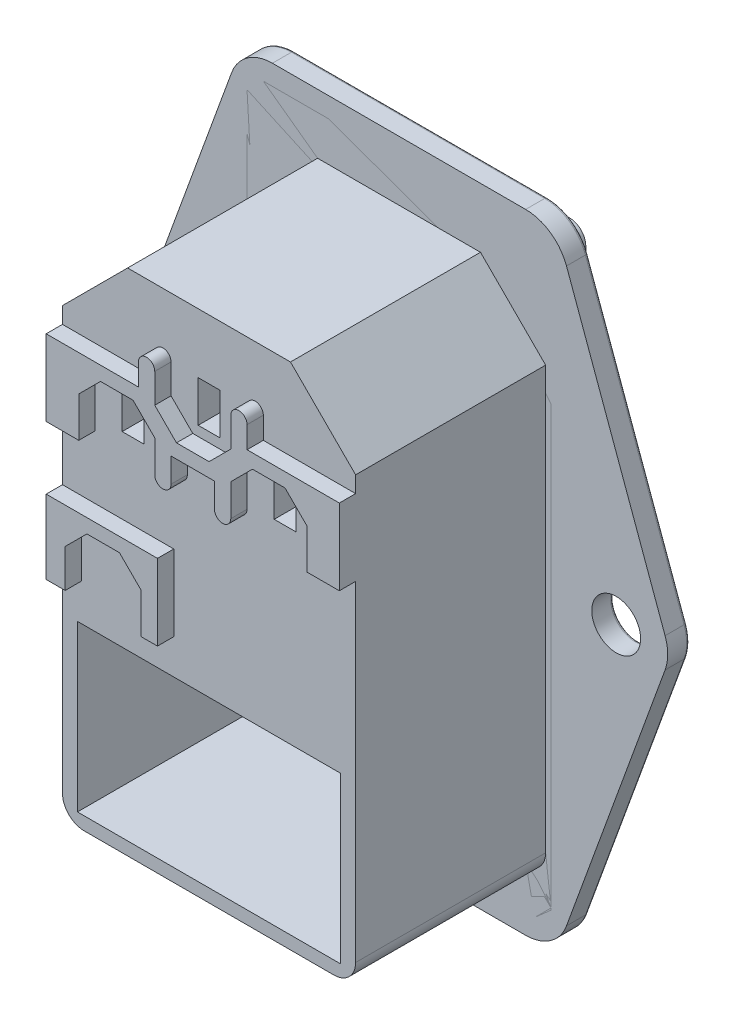
SolidWorks part; units mm, degrees
other "Mounting Face"
other "Base" parameters "D5"=2, "D1"=42.2954, "D2"=25.6387, "D3"=15.1187, "D4"=23.316, "D7"=6, "D8"=6, "D9"=0.5, "D10"=0.5, "D11"=0.5, "D12"=0.5, "D13"=0.5, "D14"=0.5, "D15"=0.5, "D16"=0.5, "D6"=2.1466, "D17"=2.5, "D18"=2.5, "D19"=4.5, "D20"=4.5, "D21"=7, "D22"=7, "D23"=31.6614, "D24"=31.6614, "D25"=2.5, "D26"=2.5, "D27"=4.5, "D28"=4.5, "D29"=9.5, "D30"=9.5, "D31"=28.4118, "D32"=28.4118, "D33"=12.05, "D34"=13.05, "D35"=13.05, "D36"=16.05, "D37"=16.05, "D38"=19.05, "D39"=19.05, "D40"=5, "D41"=5, "D42"=5, "D43"=4, "D44"=4, "D45"=4, "D46"=4, "D47"=13.55, "D48"=9.55, "D49"=5, "D50"=2, "D51"=2, "D52"=11
ref_plane "Front Plane" through (0, 0, 0) normal (0, 0, 1) x (1, 0, 0)
ref_plane "Top Plane" through (0, 0, 0) normal (0, 1, 0) x (1, 0, 0)
ref_plane "Right Plane" through (0, 0, 0) normal (1, 0, 0) x (0, 0, -1)
sketch "Sketch1" plane through (0, 0, 0) normal (0, 0, 1) x (1, 0, 0)
  line L0 (-13.5, 17.45) -> (-7.5, 23.45)
  line L1 (-7.5, 23.45) -> (7.5, 23.45)
  line L2 (-13.5, 17.45) -> (-13.5, -21.45)
  line L3 (-11.5, -23.45) -> (11.5, -23.45)
  line L4 (13.5, 17.45) -> (13.5, -21.45)
  line L5 (7.5, 23.45) -> (13.5, 17.45)
  arc A0 (11.5, -23.45) -> (13.5, -21.45) centre (11.5, -21.45) ccw
  arc A1 (-13.5, -21.45) -> (-11.5, -23.45) centre (-11.5, -21.45) ccw
  point P0 (-13.5, 23.45)
  point P3 (13.5, 23.45)
  dimension "D1" = 46.9
  dimension "D2" = 27
  dimension "D3" = 13.5
  dimension "D4" = 23.45
extrude "Base Extrude" add sketch "Sketch1" along normal blind 17.5
sketch "Sketch2" plane through (0, 0, 0) normal (0, 0, -1) x (-1, 0, 0)
  line L0 (-13.5, -21.45) -> (-13.5, 17.45) construction
  line L1 (-12.12, -7.05) -> (12.12, -7.05)
  line L2 (-12.12, -7.05) -> (-12.12, -22.25)
  line L3 (-12.12, -22.25) -> (12.12, -22.25)
  line L4 (12.12, -7.05) -> (12.12, -22.25)
  line L5 (13.5, 17.45) -> (13.5, -21.45) construction
  line L7 (11.5, -23.45) -> (-11.5, -23.45) construction
  point P4 (0, -7.05)
  dimension "D1" = 15.2
  dimension "D2" = 1.2
  dimension "D3" = 1.38
  dimension "D4" = 1.38
extrude "Switch Cavity" cut sketch "Sketch2" against normal blind 17.5
sketch "Sketch3" plane through (0, 0, 0) normal (0, 0, -1) x (-1, 0, 0)
  line L0 (-11.6622, 28.95) -> (11.6622, 28.95)
  line L1 (15.421, 26.3181) -> (24.5021, 1.3681)
  line L2 (24.5021, -1.3681) -> (15.421, -26.3181)
  line L3 (11.6622, -28.95) -> (-11.6622, -28.95)
  line L4 (-7.5, 23.45) -> (7.5, 23.45) construction
  line L5 (11.5, -23.45) -> (-11.5, -23.45) construction
  line L6 (0, 36.3877) -> (0, -35.7731) construction
  line L7 (-24.5021, -1.3681) -> (-15.421, -26.3181)
  line L8 (-15.421, 26.3181) -> (-24.5021, 1.3681)
  arc A0 (24.5021, 1.3681) -> (24.5021, -1.3681) centre (20.7433, 0) cw
  arc A1 (15.421, -26.3181) -> (11.6622, -28.95) centre (11.6622, -24.95) cw
  arc A2 (11.6622, 28.95) -> (15.421, 26.3181) centre (11.6622, 24.95) cw
  arc A3 (-15.421, -26.3181) -> (-11.6622, -28.95) centre (-11.6622, -24.95) ccw
  arc A4 (-24.5021, 1.3681) -> (-24.5021, -1.3681) centre (-20.7433, 0) ccw
  arc A5 (-11.6622, 28.95) -> (-15.421, 26.3181) centre (-11.6622, 24.95) ccw
  point P15 (25, 0)
  point P18 (14.4631, -28.95)
  point P21 (14.4631, 28.95)
  point P23 (0, -28.95)
  point P31 (0, 28.95)
  dimension "D5" = 4
  dimension "D1" = 5.5
  dimension "D2" = 5.5
  dimension "D3" = 25
  dimension "D4" = 20
extrude "Mounting Face Extrude" add sketch "Sketch3" along normal blind 2 separate body
sketch "Sketch4" plane through (0, 0, -2) normal (0, 0, -1) x (-1, 0, 0)
  line L1 (-12.5, 27.1) -> (12.5, 27.1)
  line L2 (-14, 25.6) -> (-14, -25.6)
  line L3 (-12.5, -27.1) -> (12.5, -27.1)
  line L4 (14, 25.6) -> (14, -25.6)
  arc A0 (12.5, -27.1) -> (14, -25.6) centre (12.5, -25.6) ccw
  arc A1 (-14, -25.6) -> (-12.5, -27.1) centre (-12.5, -25.6) ccw
  arc A2 (12.5, 27.1) -> (14, 25.6) centre (12.5, 25.6) cw
  arc A3 (-12.5, 27.1) -> (-14, 25.6) centre (-12.5, 25.6) ccw
  point P7 (14, -27.1)
  point P12 (14, 27.1)
  point P15 (-14, 27.1)
  dimension "D5" = 1.5
  dimension "D1" = 28
  dimension "D2" = 54.2
  dimension "D3" = 14
  dimension "D4" = 27.1
extrude "Front Face" add sketch "Sketch4" along normal blind 1.2 and the other way up to surface (2 mm away) other way up to face at (0, -14.65, 0)
sketch "Mounting Hole Positions Sketch" plane through (0, 0, -2) normal (0, 0, -1) x (-1, 0, 0)
  point P0 (-20, 0)
  point P1 (20, 0)
  dimension "D1" = 20
  dimension "D2" = 20
hole_wizard "Ø4.5 (4.5) Diameter Hole1" positions "Sketch7" profile "Sketch8" hole size "Ø4.5" standard "ANSI Metric" end condition through all
sketch "Sketch7" plane through (0, 0, -2) normal (0, 0, -1) x (-1, 0, 0)
  point P0 (-20, 0)
  point P3 (20, 0)
sketch "Sketch8" plane through (20, 0, -2) normal (1, 0, 0) x (0, 1, 0)
  line L0 (0, 0) -> (0, 19.5)
  line L1 (0, 19.5) -> (2.25, 19.5)
  line L2 (2.25, 19.5) -> (2.25, 0)
  line L5 (2.25, 0) -> (0, 0)
  line L11 (0, -6.35) -> (0, 107.95) construction
  dimension "Thru Hole Dia." = 4.5
  dimension "Thru Hole Depth" = 19.5
sketch "Sketch9" plane through (0, 0, -3.2) normal (0, 0, -1) x (-1, 0, 0)
  line L0 (-11.6622, -28.95) -> (11.6622, -28.95) construction
  line L1 (-12.5, 4.05) -> (12.5, 4.05)
  line L2 (-12.5, 4.05) -> (-12.5, -4.95)
  line L3 (-12.5, -4.95) -> (12.5, -4.95)
  line L4 (12.5, 4.05) -> (12.5, -4.95)
  line L5 (11.6622, 28.95) -> (-11.6622, 28.95) construction
  point P9 (0, 4.05)
  dimension "D1" = 9
  dimension "D2" = 24
  dimension "D3" = 24.9
  dimension "D4" = 25
extrude "Fuse Slot Cut" cut sketch "Sketch9" against normal blind 18
sketch "Sketch10" plane through (0, 0, -3.2) normal (0, 0, -1) x (-1, 0, 0)
  line L1 (-9.65, -7.05) -> (9.65, -7.05)
  line L2 (-10.65, -8.05) -> (-10.65, -21.35)
  line L3 (-9.65, -22.35) -> (9.65, -22.35)
  line L4 (10.65, -8.05) -> (10.65, -21.35)
  line L5 (-12.5, -27.1) -> (12.5, -27.1) construction
  arc A0 (9.65, -7.05) -> (10.65, -8.05) centre (9.65, -8.05) cw
  arc A1 (9.65, -22.35) -> (10.65, -21.35) centre (9.65, -21.35) ccw
  arc A2 (-10.65, -21.35) -> (-9.65, -22.35) centre (-9.65, -21.35) ccw
  arc A3 (-9.65, -7.05) -> (-10.65, -8.05) centre (-9.65, -8.05) ccw
  point P4 (0, -7.05)
  point P10 (10.65, -7.05)
  point P15 (-10.65, -22.35)
  point P18 (-10.65, -7.05)
  dimension "D4" = 1
  dimension "D1" = 21.3
  dimension "D2" = 15.3
  dimension "D3" = 4.75
extrude "Cut-Extrude3" cut sketch "Sketch10" against normal blind 2.25
sketch "Sketch11" plane through (0, 0, -0.95) normal (0, 0, -1) x (-1, 0, 0)
  line L1 (-9.5, -8.05) -> (9.5, -8.05)
  line L2 (-9.5, -8.05) -> (-9.5, -21.25)
  line L3 (-9.5, -21.25) -> (9.5, -21.25)
  line L4 (9.5, -8.05) -> (9.5, -21.25)
  line L7 (9.65, -7.05) -> (-9.65, -7.05) construction
  point P4 (0, -8.05)
  dimension "D1" = 19
  dimension "D2" = 13.2
  dimension "D3" = 1
extrude "Cut-Extrude4" cut sketch "Sketch11" against normal up to surface (18.45 mm away) up to face at (0, -14.65, 17.5)
sketch "Sketch12" plane through (0, 0, -3.2) normal (0, 0, -1) x (-1, 0, 0)
  line L0 (0, -2.1517) -> (0, 39.5345) construction
  line L1 (-6.7, 22.35) -> (6.7, 22.35)
  line L2 (6.7, 22.35) -> (12.2, 16.85)
  line L3 (12.2, 16.85) -> (12.2, 8.55)
  line L4 (9.7, 6.05) -> (-9.7, 6.05)
  line L6 (12.5, 4.05) -> (-12.5, 4.05) construction
  line L7 (14, -25.6) -> (14, 25.6) construction
  line L8 (-6.7, 22.35) -> (-12.2, 16.85)
  line L9 (-12.2, 16.85) -> (-12.2, 8.55)
  line L10 (12.5, 27.1) -> (-12.5, 27.1) construction
  arc A0 (12.2, 8.55) -> (9.7, 6.05) centre (9.7, 8.55) cw
  arc A1 (-12.2, 8.55) -> (-9.7, 6.05) centre (-9.7, 8.55) ccw
  point P8 (0, 22.35)
  point P10 (0, 6.05)
  point P25 (0, 6.05)
  dimension "D6" = 2.5
  dimension "D1" = 135
  dimension "D2" = 4.75
  dimension "D3" = 2
  dimension "D4" = 1.8
  dimension "D5" = 5.5
extrude "Cut-Extrude6" cut sketch "Sketch12" against normal blind 19.35
sketch "Sketch14" plane through (0, 0, 16.15) normal (0, 0, -1) x (-1, 0, 0)
  line L1 (-6.7, 22.35) -> (-4.7, 22.35)
  line L4 (-4.7, 22.35) -> (-4.7, 19.85)
  line L5 (-6.7, 19.85) -> (-6.7, 22.35)
  line L6 (0, 7.5639) -> (0, 19.85) construction
  line L7 (4.7, 22.35) -> (4.7, 19.85)
  line L8 (6.7, 22.35) -> (4.7, 22.35)
  line L9 (6.7, 19.85) -> (6.7, 22.35)
  arc A1 (-4.7, 19.85) -> (-6.7, 19.85) centre (-5.7, 19.85) cw
  arc A2 (4.7, 19.85) -> (6.7, 19.85) centre (5.7, 19.85) ccw
  dimension "D2" = 2
  dimension "D3" = 1
  dimension "D1" = 2.5
  dimension "D4" = 19.85
extrude "Boss-Extrude6" add sketch "Sketch14" along normal blind 2.75
sketch "Sketch15" plane through (0, 0, 16.15) normal (0, 0, -1) x (-1, 0, 0)
  line L0 (0, 30.8271) -> (0, -16.5553) construction
  line L1 (-28.4118, 12.05) -> (31.6614, 12.05) construction
  line L2 (-9.7, 6.05) -> (9.7, 6.05) construction
  line L3 (-28.4118, 16.05) -> (31.6614, 16.05) construction
  point P9 (-7, 12.05)
  point P10 (7, 12.05)
  point P11 (0, 16.05)
  dimension "D3" = 14
  dimension "D1" = 6
  dimension "D2" = 4
  dimension "D4" = 7
sketch "Sketch16" plane through (0, 0, 16.15) normal (0, 0, 1) x (1, 0, 0)
  line L0 (0, 30.8271) -> (0, -16.5553) construction
  line L1 (-28.4118, 12.05) -> (31.6614, 12.05) construction
  line L2 (2.5, 18.55) -> (2.5, 13.55)
  line L3 (-28.4118, 16.05) -> (31.6614, 16.05) construction
  line L4 (2, 19.05) -> (-2, 19.05)
  line L5 (9, 15.05) -> (5, 15.05)
  line L6 (9.5, 14.55) -> (9.5, 9.55)
  line L7 (9, 9.05) -> (5, 9.05)
  line L8 (4.5, 14.55) -> (4.5, 9.55)
  line L9 (2, 13.05) -> (-2, 13.05)
  line L10 (-2.5, 18.55) -> (-2.5, 13.55)
  line L11 (-4.5, 14.55) -> (-4.5, 9.55)
  line L12 (-5, 15.05) -> (-9, 15.05)
  line L13 (-5, 9.05) -> (-9, 9.05)
  line L14 (-9.5, 14.55) -> (-9.5, 9.55)
  arc A0 (5, 9.05) -> (4.5, 9.55) centre (5, 9.55) cw
  arc A1 (5, 15.05) -> (4.5, 14.55) centre (5, 14.55) ccw
  arc A2 (9, 15.05) -> (9.5, 14.55) centre (9, 14.55) cw
  arc A3 (9.5, 9.55) -> (9, 9.05) centre (9, 9.55) cw
  arc A4 (2, 19.05) -> (2.5, 18.55) centre (2, 18.55) cw
  arc A5 (-2, 13.05) -> (-2.5, 13.55) centre (-2, 13.55) cw
  arc A6 (2.5, 13.55) -> (2, 13.05) centre (2, 13.55) cw
  arc A7 (-2, 19.05) -> (-2.5, 18.55) centre (-2, 18.55) ccw
  arc A8 (-5, 15.05) -> (-4.5, 14.55) centre (-5, 14.55) cw
  arc A9 (-9, 9.05) -> (-9.5, 9.55) centre (-9, 9.55) cw
  arc A10 (-4.5, 9.55) -> (-5, 9.05) centre (-5, 9.55) cw
  arc A11 (-9, 15.05) -> (-9.5, 14.55) centre (-9, 14.55) ccw
  point P9 (-7, 12.05)
  point P10 (7, 12.05)
  point P11 (0, 16.05)
  point P18 (4.5, 15.05)
  point P21 (9.5, 15.05)
  point P24 (9.5, 9.05)
  dimension "D3" = 14
  dimension "D2" = 4
  dimension "D4" = 7
  dimension "D8" = 0.5
  dimension "D1" = 5
  dimension "D5" = 2.5
  dimension "D6" = 6
  dimension "D7" = 3
  dimension "D19" = 4.5
  dimension "D20" = 9.05
  dimension "D21" = 9.05
  dimension "D22" = 4
  dimension "D33" = 4
  dimension "D36" = 6
  dimension "D37" = 5
  dimension "D40" = 5
  dimension "D41" = 5
  dimension "D42" = 5
  dimension "D43" = 4
  dimension "D44" = 4
  dimension "D45" = 4
  dimension "D46" = 4
  dimension "D47" = 13.55
  dimension "D48" = 9.55
  dimension "D49" = 5
  dimension "D50" = 2
  dimension "D51" = 2
  dimension "D52" = 11
extrude "Boss-Extrude7" add sketch "Sketch16" against normal up to surface (2.75 mm away) up to face at (5.7, 20.85, 13.4)
sketch "Sketch18" plane through (0, 0, 13.4) normal (0, 0, -1) x (-1, 0, 0)
  line L0 (-28.4118, 12.05) -> (31.6614, 12.05) construction
  line L5 (-8, 13.95) -> (-6, 13.95)
  line L6 (-8, 13.95) -> (-8, 10.15)
  line L7 (-8, 10.15) -> (-6, 10.15)
  line L8 (-6, 13.95) -> (-6, 10.15)
  line L13 (6, 13.95) -> (8, 13.95)
  line L14 (8, 13.95) -> (8, 10.15)
  line L15 (6, 13.95) -> (6, 10.15)
  line L16 (6, 10.15) -> (8, 10.15)
  line L17 (-1, 17.95) -> (1, 17.95)
  line L18 (1, 17.95) -> (1, 14.15)
  line L19 (-1, 17.95) -> (-1, 14.15)
  line L20 (-1, 14.15) -> (1, 14.15)
  dimension "D1" = 3.8
  dimension "D2" = 2
  dimension "D3" = 1.9
  dimension "D4" = 1
extrude "Cut-Extrude7" cut sketch "Sketch18" against normal up to surface (4.1 mm away) up to face at (0, -14.65, 17.5)
sketch "Sketch19" plane through (0, 0, 13.4) normal (0, 0, -1) x (-1, 0, 0)
  line L0 (-5, 15.05) -> (-9, 15.05) construction
  line L1 (-8, 15.05) -> (-6, 15.05)
  line L2 (-8, 15.05) -> (-8, 9.05)
  line L3 (-8, 9.05) -> (-6, 9.05)
  line L4 (-6, 15.05) -> (-6, 9.05)
  line L5 (-5, 9.05) -> (-9, 9.05) construction
  line L6 (-1, 19.05) -> (-1, 13.05)
  line L7 (1, 19.05) -> (1, 13.05)
  line L8 (-1, 13.05) -> (1, 13.05)
  line L9 (-1, 19.05) -> (1, 19.05)
  line L10 (6, 15.05) -> (6, 9.05)
  line L11 (8, 15.05) -> (8, 9.05)
  line L12 (6, 9.05) -> (8, 9.05)
  line L13 (6, 15.05) -> (8, 15.05)
  dimension "D1" = 2
  dimension "D2" = 1
extrude "Cut-Extrude8" cut sketch "Sketch19" against normal blind 1.5
ref_plane "Plane1" through (0, -0.45, 0) normal (0, 1, 0) x (1, 0, 0)
sketch "Sketch21" plane through (0, 0, -3.2) normal (0, 0, -1) x (-1, 0, 0)
  line L0 (-9.7, 6.05) -> (9.7, 6.05) construction
  line L1 (-2.08, 6.05) -> (2.08, 6.05)
  line L2 (-2.08, 6.05) -> (-2.08, 4.05)
  line L3 (-2.08, 4.05) -> (2.08, 4.05)
  line L4 (2.08, 6.05) -> (2.08, 4.05)
  line L5 (12.5, 4.05) -> (-12.5, 4.05) construction
  dimension "D1" = 4.16
  dimension "D2" = 2.08
extrude "Cut-Extrude10" cut sketch "Sketch21" against normal up to surface (18 mm away) up to face at (0, -0.45, 14.8)
sketch "Sketch22" plane through (0, 0, 17.5) normal (0, 0, 1) x (1, 0, 0)
  line L0 (5, 15.95) -> (13.5, 15.95)
  line L1 (-13.5, 17.45) -> (-13.5, -21.45) construction
  line L3 (7.5, 23.45) -> (-7.5, 23.45) construction
  line L4 (7, 13.95) -> (7, 10.15) construction
  line L6 (13.5, 8.95) -> (10.5, 8.95)
  line L7 (10.5, 8.95) -> (10.5, 12.65)
  line L9 (8.5, 14.65) -> (5.5, 14.65)
  line L18 (-10.5, 8.95) -> (-13.5, 8.95)
  line L20 (-13.5, 8.95) -> (-13.5, 15.95)
  line L21 (10.5, 12.65) -> (8.5, 14.65)
  line L22 (6, 13.95) -> (8, 13.95) construction
  line L23 (8, 10.15) -> (6, 10.15) construction
  line L24 (3.5, 12.65) -> (5.5, 14.65)
  line L25 (3.5, 12.65) -> (3.5, 11.95)
  line L26 (0, 17.95) -> (0, 14.15) construction
  line L27 (-1, 17.95) -> (1, 17.95) construction
  line L28 (1, 14.15) -> (-1, 14.15) construction
  line L29 (-3.5, 12.65) -> (-3.5, 11.95)
  line L30 (-3.5, 12.65) -> (-5.5, 14.65)
  line L31 (-8.5, 14.65) -> (-5.5, 14.65)
  line L32 (-10.5, 12.65) -> (-8.5, 14.65)
  line L33 (-10.5, 8.95) -> (-10.5, 12.65)
  line L34 (-13.5, 8.95) -> (-10.5, 8.95)
  line L35 (-2, 11.95) -> (2, 11.95)
  line L36 (-8, 10.15) -> (-8, 13.95) construction
  line L37 (-6, 10.15) -> (-8, 10.15) construction
  line L38 (-7, 13.95) -> (-7, 10.15) construction
  line L39 (-8, 13.95) -> (-6, 13.95) construction
  line L40 (-11.75, -0.138) -> (-9.75, 1.862)
  line L41 (-4.75, -0.138) -> (-4.75, -0.838)
  line L42 (-9.75, 1.862) -> (-6.75, 1.862)
  line L43 (-4.75, -0.138) -> (-6.75, 1.862)
  line L44 (-11.75, -3.65) -> (-11.75, -0.138)
  line L45 (-11.75, -3.65) -> (-13.5, -3.65)
  line L46 (-13.5, -3.65) -> (-13.5, 3.162)
  line L47 (-13.5, 3.162) -> (-3.25, 3.162)
  line L48 (-3.25, 3.162) -> (-3.25, -3.838)
  line L49 (-3.25, -3.838) -> (-4.75, -3.838)
  line L50 (-4.75, -3.838) -> (-4.75, -0.838)
  line L51 (-13.5, 15.95) -> (-13.5, 8.95)
  line L52 (13.5, 15.95) -> (13.5, 8.95)
  line L53 (13.5, 15.95) -> (13.5, 8.95)
  line L54 (-1.5, 13.25) -> (1.5, 13.25)
  line L55 (1.5, 13.25) -> (3.5, 15.25)
  line L56 (-13.5, 15.95) -> (-5, 15.95)
  line L57 (-1.5, 13.25) -> (-3.5, 15.25)
  line L58 (-3.5, 17.95) -> (-3.5, 15.25)
  line L59 (-5, 17.95) -> (-5, 15.95)
  line L60 (-3.5, 11.95) -> (-3.5, 9.7)
  line L61 (-3.5, 11.95) -> (-3.5, 9.7)
  line L62 (-3.5, 15.95) -> (-3.5, 17.95)
  line L63 (3.5, 17.95) -> (3.5, 15.25)
  line L64 (5, 17.95) -> (5, 15.95)
  line L65 (-2, 9.7) -> (-2, 11.95)
  line L66 (2, 9.7) -> (2, 11.95)
  line L67 (3.5, 11.95) -> (3.5, 9.7)
  arc A2 (-3.5, 17.95) -> (-5, 17.95) centre (-4.25, 17.95) ccw
  arc A3 (3.5, 17.95) -> (5, 17.95) centre (4.25, 17.95) cw
  arc A4 (-3.5, 9.7) -> (-2, 9.7) centre (-2.75, 9.7) ccw
  arc A5 (3.5, 9.7) -> (2, 9.7) centre (2.75, 9.7) cw
  point P4 (13.5, 15.95)
  point P5 (0, 0)
  point P25 (0, 0)
  point P26 (-13.1383, -3.65)
  point P40 (0, 13.25)
  point P45 (-7, 12.05)
  point P78 (0, 0)
  point P79 (0, 0)
  point P80 (-13.5, 8.95)
  point P81 (0, 0)
  point P82 (0, 0)
  point P83 (0, 0)
  line M42 (-13.5, 17.45) -> (-13.5, -21.45)
  line M46 (13.5, -21.45) -> (13.5, 17.45)
  dimension "D30" = 1.5
  dimension "D10" = 1.5
  dimension "D1" = 7.5
  dimension "D3" = 7
  dimension "D4" = 3
  dimension "D5" = 3
  dimension "D2" = 1.3
  dimension "D6" = 135
  dimension "D7" = 2
  dimension "D8" = 2.5
  dimension "D13" = 1.3
  dimension "D14" = 1.75
  dimension "D15" = 1.5
  dimension "D19" = 3.25
  dimension "D16" = 1.25
  dimension "D17" = 3.25
  dimension "D18" = 1.75
  dimension "D24" = 10.288
  dimension "D25" = 10.288
  dimension "D20" = 6.988
  dimension "D21" = 10.988
  dimension "D22" = 13.8
  dimension "D23" = 13.988
  dimension "D26" = 4
  dimension "D9" = 1.8
  dimension "D27" = 1.3
  dimension "D28" = 3
  dimension "D31" = 2
  dimension "D32" = 135
  dimension "D29" = 8.5
  dimension "D33" = 2.7
  dimension "D11" = 2.25
  dimension "D12" = 3.1
extrude "Boss-Extrude10" add sketch "Sketch22" along normal blind 1.5 contours L50 L49 L48 L47 L45 L44 L40 L42 L43 L41 M42 | A5 L67 L25 L24 L9 L21 L7 L6 L0 L64 A3 L63 L55 L54 L57 L58 A2 L59 L56 L18 L33 L32 L31 L30 L29 L60 A4 L65 L35 L66 M46 M42
fillet "Mounting Face Fillets" radius 0.25 34 edges at (-19.9615, -13.8431, -2) (-13.9565, -28.2266, -2) (0, -28.95, -2) (13.9565, -28.2266, -2) (19.9615, -13.8431, -2) (24.7433, 0, -2) (19.9615, 13.8431, -2) (13.9565, 28.2266, -2) (0, 28.95, -2) (-13.9565, 28.2266, -2) (-19.9615, 13.8431, -2) (-24.7433, 0, -2) (-22.25, 0, -2) (17.75, 0, -2) (-12.5, -0.45, -2) (0, 4.05, -2) (12.5, -0.45, -2) (0, -4.95, -2) (10.3571, -7.3429, -2) (10.65, -14.7, -2) (10.3571, -22.0571, -2) (0, -22.35, -2) (-10.3571, -22.0571, -2) (-10.65, -14.7, -2) (-10.3571, -7.3429, -2) (0, -7.05, -2) (9.45, 19.6, -2) (12.2, 12.7, -2) (11.4678, 6.7822, -2) (0, 6.05, -2) (-11.4678, 6.7822, -2) (-12.2, 12.7, -2) (-9.45, 19.6, -2) (0, 22.35, -2)
equation "\"D3@Sketch1\"=\"D2@Sketch1\"/2"
equation "\"D4@Sketch1\"=\"D1@Sketch1\"/2"
equation "\"D3@Sketch4\"=\"D1@Sketch4\"/2"
equation "\"D4@Sketch4\"=\"D2@Sketch4\"/2"
equation "\"D4@Sketch15\"=\"D3@Sketch15\"/2"
equation "\"D5@Sketch16\"=\"D1@Sketch16\"/2"
equation "\"D7@Sketch16\"=\"D6@Sketch16\"/2"
equation "\"D3@Sketch18\"=\"D1@Sketch18\"/2"
equation "\"D4@Sketch18\"=\"D2@Sketch18\"/2"
equation "\"D2@Sketch21\"=\"D1@Sketch21\"/2"
equation "\"D5@Sketch22\"=\"D4@Sketch22\""
equation "\"D27@Sketch22\"=\"D2@Sketch22\""
